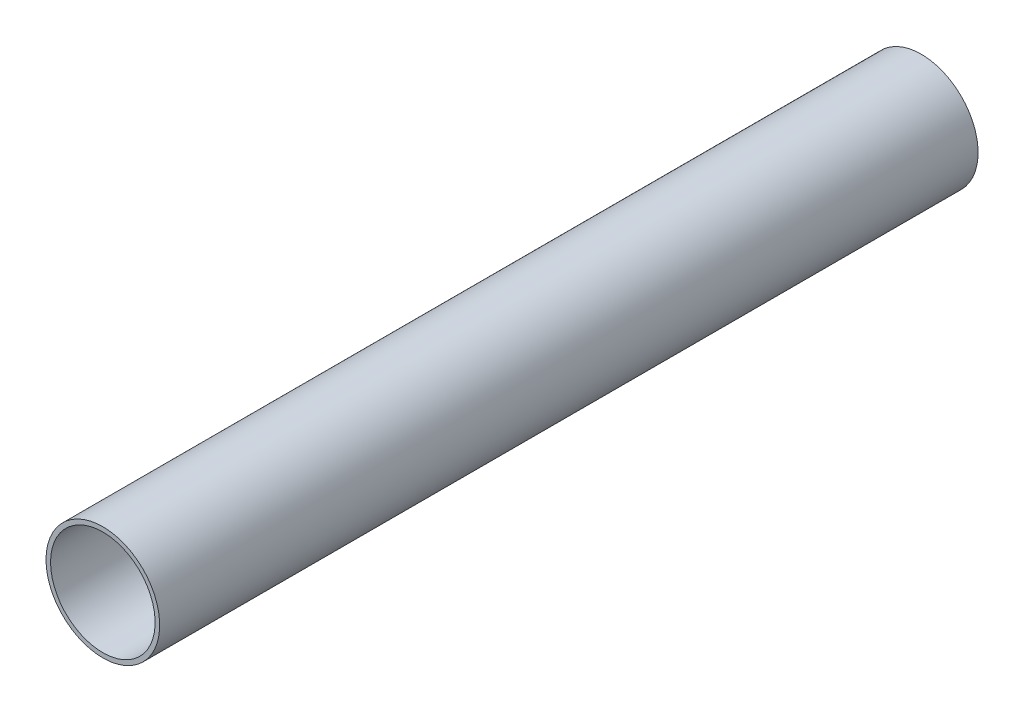
SolidWorks part; units mm, degrees
material "Thornel Mat VMA"
ref_plane "前视基准面" through (0, 0, 0) normal (0, 0, 1) x (1, 0, 0)
ref_plane "上视基准面" through (0, 0, 0) normal (0, 1, 0) x (1, 0, 0)
ref_plane "右视基准面" through (0, 0, 0) normal (1, 0, 0) x (0, 0, -1)
sketch "草图1" plane through (0, 0, 0) normal (0, 0, 1) x (1, 0, 0)
  circle A0 centre (0, 0) radius 11.5
  circle A1 centre (0, 0) radius 12.5
  dimension "D1" = 25
  dimension "D2" = 1
extrude "凸台-拉伸1" add sketch "草图1" along normal blind 180
